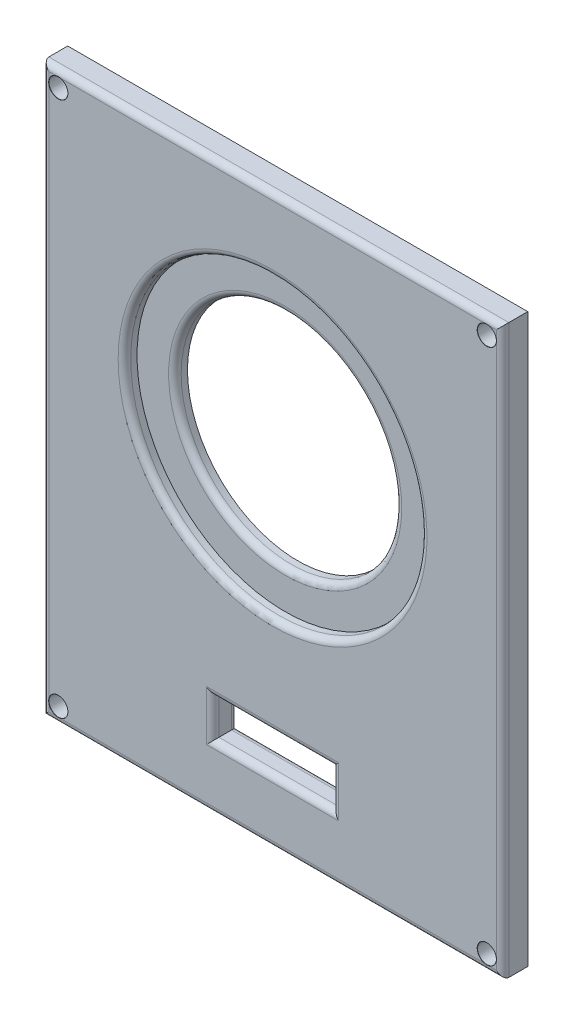
SolidWorks part; units mm, degrees
ref_plane "Front Plane" through (0, 0, 0) normal (0, 0, 1) x (1, 0, 0)
ref_plane "Top Plane" through (0, 0, 0) normal (0, 1, 0) x (1, 0, 0)
ref_plane "Right Plane" through (0, 0, 0) normal (1, 0, 0) x (0, 0, -1)
sketch "草图1" plane through (0, 0, 0) normal (0, 0, 1) x (1, 0, 0)
  line L1 (0, 0) -> (73, 0)
  line L2 (0, 0) -> (0, 90)
  line L3 (0, 90) -> (73, 90)
  line L4 (73, 0) -> (73, 90)
  dimension "D1" = 73
  dimension "D2" = 90
extrude "凸台-拉伸1" add sketch "草图1" along normal blind 4
sketch "草图2" plane through (0, 0, 4) normal (0, 0, 1) x (1, 0, 0)
  line L0 (0, 90) -> (0, 0) construction
  line L1 (2.5, 87.5) -> (70.5, 87.5)
  line L2 (2.5, 87.5) -> (2.5, 2.5)
  line L3 (2.5, 2.5) -> (70.5, 2.5)
  line L4 (70.5, 87.5) -> (70.5, 2.5)
  line L5 (0, 0) -> (73, 0) construction
  line L6 (73, 0) -> (73, 90) construction
  line L7 (73, 90) -> (0, 90) construction
  dimension "D1" = 2.5
  dimension "D2" = 2.5
  dimension "D3" = 2.5
  dimension "D4" = 2.5
hole_wizard "大小mm 暗销孔1" positions "草图3" profile "草图4" hole size "Ø3.0" standard "GB" end condition up to next
sketch "草图3" plane through (0, 0, 4) normal (0, 0, 1) x (1, 0, 0)
  point P0 (2.5, 2.5)
  point P3 (70.5, 2.5)
  point P6 (70.5, 87.5)
  point P9 (2.5, 87.5)
sketch "草图4" plane through (2.5, 2.5, 4) normal (1, 0, 0) x (0, -1, 0)
  line L0 (0, 0) -> (0, 4)
  line L1 (0, 4) -> (1.5, 4)
  line L2 (1.5, 4) -> (1.5, 0.021)
  line L3 (1.5, 0.021) -> (1.525, 0)
  line L5 (1.525, 0) -> (0, 0)
  line L6 (-1.5, 0.021) -> (-1.525, 0) construction
  line L11 (0, -6.35) -> (0, 107.95) construction
  dimension "通孔孔直径" = 3
  dimension "通孔孔深度" = 4
  dimension "近端锥形沉头孔直径" = 3.05
  dimension "近端锥形沉头孔角度" = 100
sketch "草图5" plane through (0, 0, 4) normal (0, 0, 1) x (1, 0, 0)
  line L0 (36.5, 0) -> (36.5, 98.7728) construction
  line L1 (0, 0) -> (73, 0) construction
  line L2 (73, 90) -> (0, 90) construction
  circle A0 centre (36.5, 55) radius 20
  circle A1 centre (36.5, 55) radius 17.5
  dimension "D2" = 40
  dimension "D3" = 35
  dimension "D1" = 35
extrude "切除-拉伸3" cut sketch "草图5" against normal through all contours A1
sketch "草图9" plane through (0, 0, 4) normal (0, 0, 1) x (1, 0, 0)
  circle A0 centre (36.5, 55) radius 23.5
  dimension "D1" = 47
extrude "切除-拉伸4" cut sketch "草图9" against normal blind 2
sketch "草图10" plane through (0, 0, 4) normal (0, 0, 1) x (1, 0, 0)
  line L0 (0, 90) -> (0, 0) construction
  line L1 (27, 16) -> (46, 16)
  line L2 (27, 16) -> (27, 10)
  line L3 (27, 10) -> (46, 10)
  line L4 (46, 16) -> (46, 10)
  line L5 (73, 0) -> (73, 90) construction
  line L6 (0, 0) -> (73, 0) construction
  dimension "D1" = 27
  dimension "D2" = 27
  dimension "D3" = 6
  dimension "D4" = 10
extrude "切除-拉伸5" cut sketch "草图10" against normal blind 10
fillet "圆角1" radius 1 14 edges at (46, 13, 0) (36.5, 16, 0) (27, 13, 0) (36.5, 10, 0) (46, 13, 4) (27, 13, 4) (36.5, 10, 4) (36.5, 16, 4) (60, 55, 4) (54, 55, 2) (73, 45, 4) (36.5, 0, 4) (36.5, 90, 4) (0, 45, 4)
